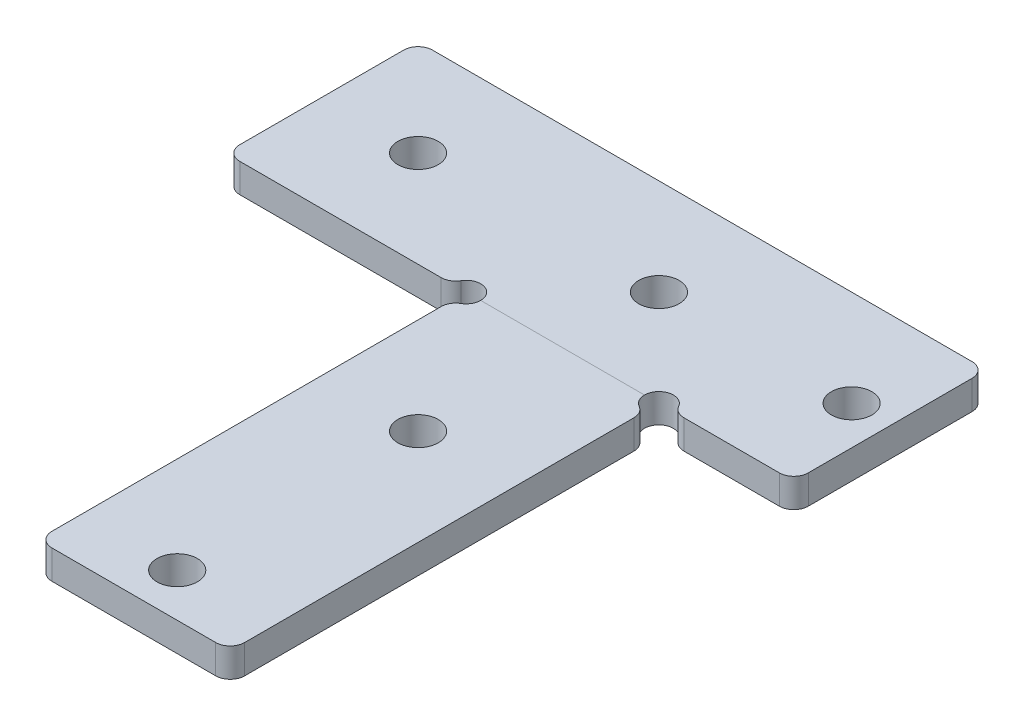
SolidWorks part; units mm, degrees
material "A-玻璃纤维"
ref_plane "前视基准面" through (0, 0, 0) normal (0, 0, 1) x (1, 0, 0)
ref_plane "上视基准面" through (0, 0, 0) normal (0, 1, 0) x (1, 0, 0)
ref_plane "右视基准面" through (0, 0, 0) normal (1, 0, 0) x (0, 0, -1)
sketch "草图1" plane through (0, 0, 0) normal (0, 1, 0) x (1, 0, 0)
  line L0 (-25, 0) -> (20, 0) construction
  line L1 (0, 0) -> (0, -50) construction
  line L2 (-35, 10) -> (24, 10)
  line L3 (24, 10) -> (24, -10)
  line L4 (24, -10) -> (10, -10)
  line L5 (10, -10) -> (10, -60)
  line L6 (10, -60) -> (-10, -60)
  line L7 (-10, -60) -> (-10, -10)
  line L8 (-10, -10) -> (-35, -10)
  line L9 (-35, -10) -> (-35, 10)
  circle A0 centre (0, 0) radius 2.1
  circle A1 centre (20, 0) radius 2.1
  circle A2 centre (-25, 0) radius 2.1
  circle A3 centre (0, -25) radius 2.1
  circle A4 centre (0, -50) radius 2.1
  point P18 (-35, 0)
  dimension "D1" = 20
  dimension "D2" = 25
  dimension "D3" = 25
  dimension "D4" = 25
  dimension "D5" = 4.2
  dimension "D7" = 4
  dimension "D8" = 10
  dimension "D6" = 20
  dimension "D9" = 20
extrude "凸台-拉伸1" add sketch "草图1" along normal blind 3
sketch "草图2" plane through (0, 3, 0) normal (0, 1, 0) x (1, 0, 0)
  line L0 (10, -60) -> (10, -10) construction
  line L1 (-10, -60) -> (10, -60)
  line L2 (-10, -60) -> (-10, -54.5)
  line L3 (-10, -54.5) -> (10, -54.5)
  line L4 (10, -60) -> (10, -54.5)
  line L5 (0, -54.5) -> (0, -60) construction
  line L6 (-10, -57.25) -> (10, -57.25) construction
  circle A0 centre (0, -50) radius 2.1 construction
  point P124 (0, -57.25)
  dimension "D1" = 4.5
extrude "切除-拉伸1" cut sketch "草图2" against normal blind 3
sketch "草图3" plane through (0, 3, 0) normal (0, 1, 0) x (1, 0, 0)
  circle A2 centre (10, -10) radius 1.5
  circle A3 centre (-10, -10) radius 1.5
  dimension "D1" = 3
extrude "切除-拉伸3" cut sketch "草图3" against normal blind 3
fillet "圆角2" radius 1.5 10 edges at (10, 1.5, 54.5) (-10, 1.5, 54.5) (-10, 1.5, 11.5) (-11.5, 1.5, 10) (-35, 1.5, 10) (-35, 1.5, -10) (24, 1.5, 10) (11.5, 1.5, 10) (10, 1.5, 11.5) (24, 1.5, -10)
sketch "草图4" plane through (0, 3, 0) normal (0, 1, 0) x (1, 0, 0)
  line L0 (8.5, -54.5) -> (-8.5, -54.5) construction
  line L1 (-12.5981, -10) -> (12.5981, -10)
  line L2 (-12.5981, -10) -> (-12.5981, -54.5)
  line L3 (-12.5981, -54.5) -> (12.5981, -54.5)
  line L4 (12.5981, -10) -> (12.5981, -54.5)
  line L5 (0, -54.5) -> (0, -10) construction
  line L6 (-12.5981, -32.25) -> (12.5981, -32.25) construction
  point P196 (0, -32.25)
split line "分割线1"
